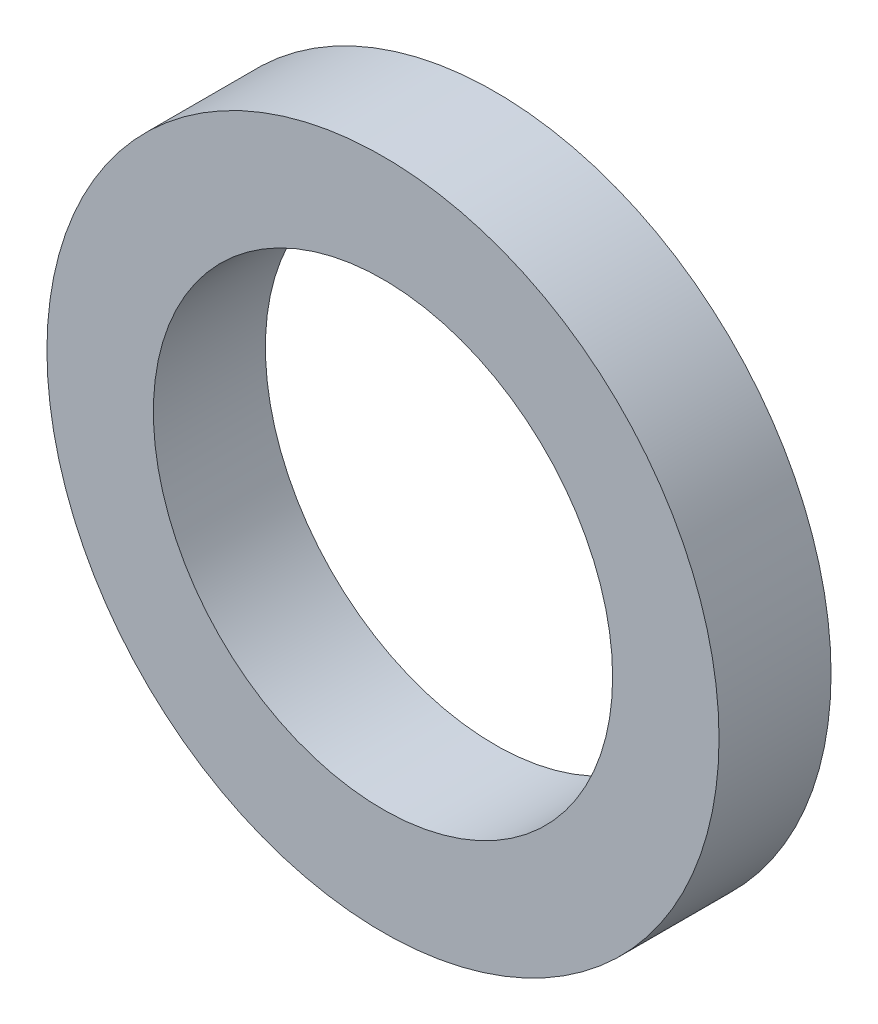
SolidWorks part; units mm, degrees
material "环氧树脂,未充填"
ref_plane "前视基准面" through (0, 0, 0) normal (0, 0, 1) x (1, 0, 0)
ref_plane "上视基准面" through (0, 0, 0) normal (0, 1, 0) x (1, 0, 0)
ref_plane "右视基准面" through (0, 0, 0) normal (1, 0, 0) x (0, 0, -1)
sketch "草图1" plane through (0, 0, 0) normal (0, 0, 1) x (1, 0, 0)
  circle A0 centre (0, 0) radius 4.1
  circle A1 centre (0, 0) radius 6
  dimension "D1" = 8.2
  dimension "D2" = 12
extrude "凸台-拉伸1" add sketch "草图1" along normal blind 2
